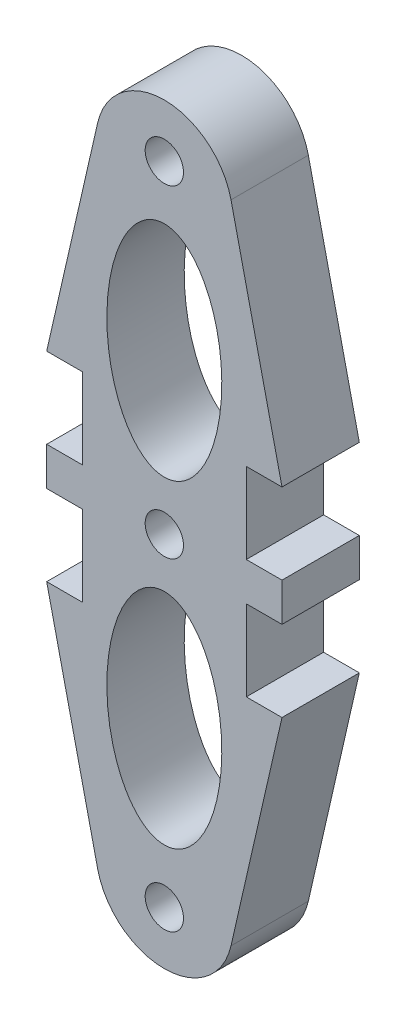
SolidWorks part; units mm, degrees
material "Acrylic (Medium-high impact)"
ref_plane "Front Plane" through (0, 0, 0) normal (0, 0, 1) x (1, 0, 0)
ref_plane "Top Plane" through (0, 0, 0) normal (0, 1, 0) x (1, 0, 0)
ref_plane "Right Plane" through (0, 0, 0) normal (1, 0, 0) x (0, 0, -1)
sketch "Sketch1" plane through (0, 0, 0) normal (0, 0, 1) x (1, 0, 0)
  line L0 (-213.0416, 464.8524) -> (49786.9584, 464.8524) construction
  line L1 (781.4592, 464.8524) -> (778.7592, 464.8524)
  line L2 (781.4592, 464.8524) -> (781.4592, 470.9524)
  line L3 (781.4592, 470.9524) -> (778.7592, 470.9524)
  line L4 (787.6592, -515.9255) -> (787.6592, 49484.0745) construction
  line L5 (-215.2216, 463.4024) -> (49784.7784, 463.4024) construction
  line L6 (793.8592, 470.9524) -> (793.8592, 487.8374) construction
  line L7 (-217.5077, 461.9524) -> (49782.4923, 461.9524) construction
  line L8 (786.2092, -537.0976) -> (786.2092, 49462.9024) construction
  line L9 (789.1092, -536.5976) -> (789.1092, 49463.4024) construction
  line L10 (793.8592, 464.8524) -> (796.5592, 464.8524)
  line L11 (781.4592, 470.9524) -> (793.8592, 470.9524) construction
  line L12 (793.8592, 470.9524) -> (796.5592, 470.9524)
  line L13 (793.8592, 464.8524) -> (793.8592, 470.9524)
  line L14 (778.7592, 464.8524) -> (778.7592, 461.9524)
  line L15 (796.5592, 464.8524) -> (796.5592, 461.9524)
  line L16 (786.2092, 487.8374) -> (782.615, 487.8374) construction
  line L17 (781.4592, 461.9524) -> (778.7592, 461.9524)
  line L18 (793.8592, 470.9524) -> (793.1379, 470.9192) construction
  line L19 (781.4592, 455.8524) -> (778.7592, 455.8524)
  line L20 (781.4592, 461.9524) -> (781.4592, 455.8524)
  line L21 (793.8592, 461.9524) -> (796.5592, 461.9524)
  line L22 (793.8592, 461.9524) -> (793.8592, 455.8524)
  line L23 (793.8592, 455.8524) -> (796.5592, 455.8524)
  line L24 (778.7592, 470.9524) -> (782.615, 487.8374)
  line L25 (792.7033, 487.8374) -> (796.5592, 470.9524)
  line L26 (792.7033, 438.9674) -> (796.5592, 455.8524)
  line L27 (789.1092, 438.9674) -> (792.7033, 438.9674) construction
  line L28 (786.2092, 438.9674) -> (782.615, 438.9674) construction
  line L29 (778.7592, 455.8524) -> (782.615, 438.9674)
  line L35 (789.1092, 487.8374) -> (792.7033, 487.8374) construction
  arc A0 (782.615, 487.8374) -> (792.7033, 487.8374) centre (787.6592, 486.6855) cw
  arc A1 (782.615, 438.9674) -> (792.7033, 438.9674) centre (787.6592, 440.1192) ccw
  circle A3 centre (787.6592, 487.8374) radius 1.45
  circle A5 centre (787.6592, 438.9674) radius 1.45
  circle A6 centre (787.6592, 463.4024) radius 1.45
  ellipse E0 centre (787.6592, 475.4481) end of major axis (787.6592, 483.7502) minor radius 4.3465
  ellipse E1 centre (787.6592, 451.3566) end of major axis (787.6592, 443.0545) minor radius 4.3465
  point P10 (778.7592, 463.4024)
  point P19 (796.5592, 463.4024)
  dimension "D1" = 2.9
  dimension "D3" = 6.1
  dimension "D10" = 5.174
  dimension "D2" = 2.7
  dimension "D4" = 24.435
  dimension "D5" = 12.4
  dimension "D6" = 16.6042
  dimension "D7" = 8.693
  dimension "D8" = 2.2937
extrude "Boss-Extrude1" add sketch "Sketch1" along normal blind 5.85
